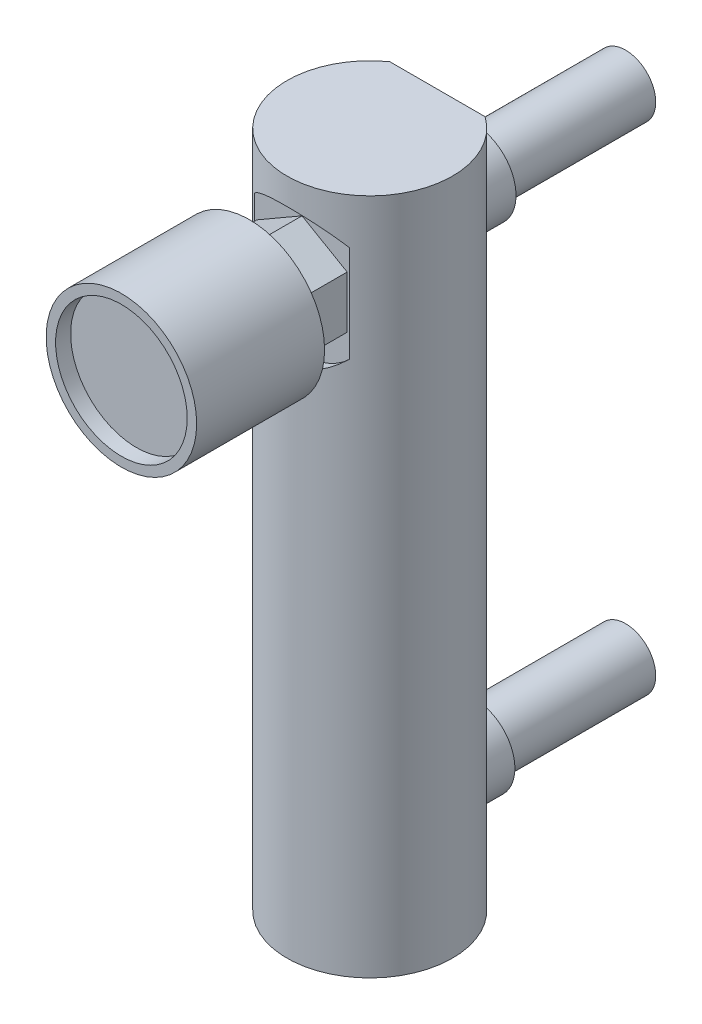
SolidWorks part; units mm, degrees
material "ABS PC"
ref_plane "Alzado" through (0, 0, 0) normal (0, 0, 1) x (1, 0, 0)
ref_plane "Planta" through (0, 0, 0) normal (0, 1, 0) x (1, 0, 0)
ref_plane "Vista lateral" through (0, 0, 0) normal (1, 0, 0) x (0, 0, -1)
sketch "Croquis1" plane through (0, 0, 0) normal (0, 1, 0) x (1, 0, 0)
  line L1 (-26.5617, 9) -> (26.5617, 9)
  line L2 (-26.5617, 9) -> (-26.5617, -31)
  line L3 (-26.5617, -31) -> (26.5617, -31)
  line L4 (26.5617, 9) -> (26.5617, -31)
  line L5 (-26.5617, 9) -> (26.5617, -31) construction
  line L6 (-26.5617, -31) -> (26.5617, 9) construction
  circle A0 centre (0, 0) radius 11
  point P3 (0, -11)
  dimension "D1" = 22
  dimension "D2" = 40
extrude "Saliente-Extruir1" add sketch "Croquis1" along normal blind 90 contours L1 A0
ref_plane "Plano1" through (0, 0, 9) normal (0, 0, -1) x (-1, 0, 0)
sketch "Croquis3" plane through (0, 0, 9) normal (0, 0, -1) x (-1, 0, 0)
  line L0 (11, 90) -> (-11, 90) construction
  line L2 (6.5, 84.406) -> (-6.5, 84.406)
  line L3 (6.5, 84.406) -> (6.5, 70.594)
  line L4 (6.5, 70.594) -> (-6.5, 70.594)
  line L5 (-6.5, 84.406) -> (-6.5, 70.594)
  line L6 (6.5, 84.406) -> (-6.5, 70.594) construction
  line L7 (6.5, 70.594) -> (-6.5, 84.406) construction
  circle A0 centre (0, 77.5) radius 9
  dimension "D3" = 18
  dimension "D1" = 12.5
  dimension "D2" = 13
extrude "Cortar-Extruir1" cut sketch "Croquis3" against normal through all contours L3 A0 L5 | L2 A0 | L4 A0
sketch "Croquis4" plane through (0, 0, 9) normal (0, 0, 1) x (1, 0, 0)
  line L1 (0, 70.5718) -> (6, 74.0359)
  line L2 (6, 74.0359) -> (6, 80.9641)
  line L3 (6, 80.9641) -> (0, 84.4282)
  line L4 (0, 84.4282) -> (-6, 80.9641)
  line L5 (-6, 80.9641) -> (-6, 74.0359)
  line L6 (-6, 74.0359) -> (0, 70.5718)
  circle A0 centre (0, 77.5) radius 6 construction
  dimension "D1" = 12
extrude "Saliente-Extruir2" add sketch "Croquis4" along normal blind 5
sketch "Croquis5" plane through (0, 0, 14) normal (0, 0, 1) x (1, 0, 0)
  circle A0 centre (0, 77.5) radius 1.7007
extrude "Saliente-Extruir3" add sketch "Croquis5" along normal blind 19
sketch "Croquis6" plane through (0, 0, 33) normal (0, 0, 1) x (1, 0, 0)
  circle A0 centre (0, 77.5) radius 10
  dimension "D1" = 20
extrude "Saliente-Extruir4" add sketch "Croquis6" against normal blind 17
sketch "Croquis7" plane through (0, 0, 33) normal (0, 0, 1) x (1, 0, 0)
  circle A0 centre (0, 77.5) radius 8.7451
extrude "Cortar-Extruir2" cut sketch "Croquis7" against normal blind 2
ref_plane "Plano2" through (0, 11, 0) normal (0, -1, 0) x (-1, 0, 0)
sketch "Croquis8" plane through (0, 11, 0) normal (0, -1, 0) x (-1, 0, 0)
  circle A0 centre (0, 0) radius 4.5822
extrude "Cortar-Extruir3" cut sketch "Croquis8" against normal blind 72
sketch "Croquis9" plane through (0, 0, -9) normal (0, 0, -1) x (-1, 0, 0)
  line L0 (0, 0) -> (0, 90) construction
  line L1 (6.3246, 0) -> (-6.3246, 0) construction
  line L2 (6.3246, 90) -> (-6.3246, 90) construction
  line L3 (0, 45) -> (36.3926, 45) construction
  circle A0 centre (0, 78) radius 4
  circle A1 centre (0, 12) radius 4
  point P8 (0, 45)
  dimension "D1" = 8
  dimension "D2" = 33
extrude "Saliente-Extruir5" add sketch "Croquis9" along normal blind 25
sketch "Croquis10" plane through (0, 0, -9) normal (0, 0, -1) x (-1, 0, 0)
  circle A0 centre (0, 78) radius 5.4361
  circle A1 centre (0, 12) radius 5.2824
extrude "Saliente-Extruir6" add sketch "Croquis10" along normal blind 5
